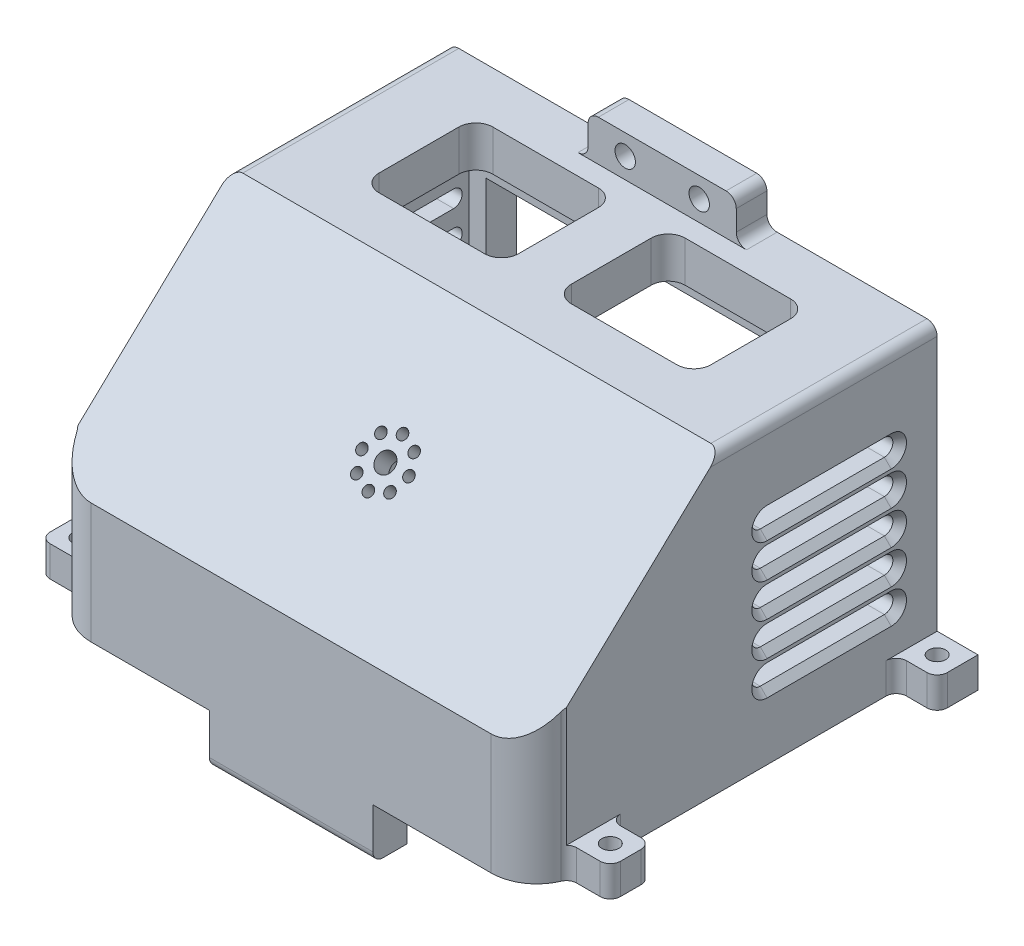
SolidWorks part; units mm, degrees
ref_plane "Front Plane" through (0, 0, 0) normal (0, 0, 1) x (1, 0, 0)
ref_plane "Top Plane" through (0, 0, 0) normal (0, 1, 0) x (1, 0, 0)
ref_plane "Right Plane" through (0, 0, 0) normal (1, 0, 0) x (0, 0, -1)
sketch "Sketch1" plane through (0, 0, 0) normal (0, 1, 0) x (1, 0, 0)
  line L0 (-83.8165, 105.1191) -> (-83.8165, 99.1191)
  line L1 (-80.8165, 96.1191) -> (-74.8165, 96.1191)
  line L2 (-71.8165, 93.1191) -> (-71.8165, 14.1191)
  line L3 (-74.8165, 11.1191) -> (-80.8165, 11.1191)
  line L4 (-83.8165, 8.1191) -> (-83.8165, -9.8809)
  line L5 (-80.8165, -12.8809) -> (-74.8165, -12.8809)
  line L6 (-71.8165, -15.8809) -> (-71.8165, -93.8809)
  line L7 (-74.8165, -96.8809) -> (-80.8165, -96.8809)
  line L8 (-83.8165, -99.8809) -> (-83.8165, -105.8809)
  line L9 (-80.8165, -108.8809) -> (-73.9507, -108.8809)
  line L10 (-58.8271, -118.8809) -> (-25.0665, -118.8809)
  line L12 (-25.0665, -108.8809) -> (-58.5665, -108.8809)
  line L13 (-58.5665, -108.8809) -> (-58.5665, -78.8809)
  line L14 (-58.5665, -78.8809) -> (-56.8165, -78.8809)
  line L15 (-56.8165, -78.8809) -> (-56.8165, 108.1191)
  line L16 (-56.8165, 108.1191) -> (56.6835, 108.1191)
  line L17 (56.6835, 108.1191) -> (56.6835, -78.8809)
  line L18 (56.6835, -78.8809) -> (58.4335, -78.8809)
  line L19 (58.4335, -78.8809) -> (58.4335, -108.8809)
  line L20 (58.4335, -108.8809) -> (24.9335, -108.8809)
  line L22 (24.9335, -118.8809) -> (58.6942, -118.8809)
  line L23 (73.8178, -108.8809) -> (80.6835, -108.8809)
  line L24 (83.6835, -105.8809) -> (83.6835, -99.8809)
  line L25 (80.6835, -96.8809) -> (74.6835, -96.8809)
  line L26 (71.6835, -93.8809) -> (71.6835, -15.8809)
  line L27 (74.6835, -12.8809) -> (80.6835, -12.8809)
  line L28 (83.6835, -9.8809) -> (83.6835, 8.1191)
  line L29 (80.6835, 11.1191) -> (74.6835, 11.1191)
  line L30 (71.6835, 14.1191) -> (71.6835, 93.1191)
  line L31 (74.6835, 96.1191) -> (80.6835, 96.1191)
  line L32 (83.6835, 99.1191) -> (83.6835, 105.1191)
  line L33 (80.6835, 108.1191) -> (73.5655, 108.1191)
  line L34 (56.6835, 118.1191) -> (-56.8165, 118.1191)
  line L35 (-73.6984, 108.1191) -> (-80.8165, 108.1191)
  line L36 (-83.8165, -0.8809) -> (83.6835, -0.8809)
  line L37 (-71.8165, -15.8809) -> (-71.8165, -0.8809)
  line L38 (71.6835, -15.8809) -> (71.6835, -0.8809)
  line L39 (-71.8165, -93.8809) -> (-71.8165, -109.7726)
  line L40 (71.6835, -93.8809) -> (71.6835, -109.7726)
  line L41 (-56.8165, -78.8809) -> (-56.8165, -108.8809)
  line L42 (56.6835, -78.8809) -> (56.6835, -108.8809)
  line L43 (-56.8165, -9.8809) -> (56.6835, -9.8809)
  line L44 (-25.0665, -108.8809) -> (24.9335, -108.8809)
  line L45 (-25.0665, -118.8809) -> (24.9335, -118.8809)
  arc A0 (-83.8165, 99.1191) -> (-80.8165, 96.1191) centre (-80.8165, 99.1191) ccw
  arc A1 (-71.8165, 93.1191) -> (-74.8165, 96.1191) centre (-74.8165, 93.1191) ccw
  arc A2 (-74.8165, 11.1191) -> (-71.8165, 14.1191) centre (-74.8165, 14.1191) ccw
  arc A3 (-80.8165, 11.1191) -> (-83.8165, 8.1191) centre (-80.8165, 8.1191) ccw
  arc A4 (-83.8165, -9.8809) -> (-80.8165, -12.8809) centre (-80.8165, -9.8809) ccw
  arc A5 (-71.8165, -15.8809) -> (-74.8165, -12.8809) centre (-74.8165, -15.8809) ccw
  arc A6 (-74.8165, -96.8809) -> (-71.8165, -93.8809) centre (-74.8165, -93.8809) ccw
  arc A7 (-80.8165, -96.8809) -> (-83.8165, -99.8809) centre (-80.8165, -99.8809) ccw
  arc A8 (-83.8165, -105.8809) -> (-80.8165, -108.8809) centre (-80.8165, -105.8809) ccw
  arc A9 (-71.1903, -110.7062) -> (-73.9507, -108.8809) centre (-73.9507, -111.8809) ccw
  arc A10 (-71.1903, -110.7062) -> (-58.8271, -118.8809) centre (-58.8271, -105.4448) ccw
  arc A11 (58.6942, -118.8809) -> (71.0574, -110.7062) centre (58.6942, -105.4448) ccw
  arc A12 (73.8178, -108.8809) -> (71.0574, -110.7062) centre (73.8178, -111.8809) ccw
  arc A13 (80.6835, -108.8809) -> (83.6835, -105.8809) centre (80.6835, -105.8809) ccw
  arc A14 (83.6835, -99.8809) -> (80.6835, -96.8809) centre (80.6835, -99.8809) ccw
  arc A15 (71.6835, -93.8809) -> (74.6835, -96.8809) centre (74.6835, -93.8809) ccw
  arc A16 (74.6835, -12.8809) -> (71.6835, -15.8809) centre (74.6835, -15.8809) ccw
  arc A17 (80.6835, -12.8809) -> (83.6835, -9.8809) centre (80.6835, -9.8809) ccw
  arc A18 (83.6835, 8.1191) -> (80.6835, 11.1191) centre (80.6835, 8.1191) ccw
  arc A19 (71.6835, 14.1191) -> (74.6835, 11.1191) centre (74.6835, 14.1191) ccw
  arc A20 (74.6835, 96.1191) -> (71.6835, 93.1191) centre (74.6835, 93.1191) ccw
  arc A21 (80.6835, 96.1191) -> (83.6835, 99.1191) centre (80.6835, 99.1191) ccw
  arc A22 (83.6835, 105.1191) -> (80.6835, 108.1191) centre (80.6835, 105.1191) ccw
  arc A23 (70.9345, 109.6775) -> (73.5655, 108.1191) centre (73.5655, 111.1191) ccw
  arc A24 (70.9345, 109.6775) -> (56.6835, 118.1191) centre (56.6835, 101.8691) ccw
  arc A25 (-56.8165, 118.1191) -> (-71.0675, 109.6775) centre (-56.8165, 101.8691) ccw
  arc A26 (-73.6984, 108.1191) -> (-71.0675, 109.6775) centre (-73.6984, 111.1191) ccw
  arc A27 (-80.8165, 108.1191) -> (-83.8165, 105.1191) centre (-80.8165, 105.1191) ccw
  dimension "D1" = 9
extrude "Boss-Extrude1" add sketch "Sketch1" along normal blind 87 contours A12 L40 L26 L38 L36 L17 L18 L19 L20 L44 L12 L13 L14 L15 L37 L6 L39 A9 A10 L10 L45 L22 A11 | L15 L43 L17 L36 | L18 L42 L20 L19 | L41 L14 L13 L12
sketch "Sketch2" plane through (0, 0, 0) normal (0, -1, 0) x (1, 0, 0)
  line L0 (-80.8165, 108.8809) -> (-73.9507, 108.8809) construction
  line L1 (73.8178, 108.8809) -> (80.6835, 108.8809) construction
  line L2 (83.6835, 105.8809) -> (83.6835, 99.8809) construction
  line L3 (80.6835, 96.8809) -> (74.6835, 96.8809) construction
  line L4 (58.6942, 118.8809) -> (-58.8271, 118.8809)
  line L5 (-71.8165, 109.7726) -> (-71.8165, 0.8809)
  line L6 (-71.8165, 0.8809) -> (71.6835, 0.8809)
  line L7 (71.6835, 0.8809) -> (71.6835, 109.7726)
  line L8 (58.6942, 118.8809) -> (-58.8271, 118.8809)
  line L9 (-71.8165, 109.7726) -> (-71.8165, 0.8809)
  line L10 (-71.8165, 0.8809) -> (71.6835, 0.8809)
  line L11 (71.6835, 0.8809) -> (71.6835, 109.7726)
  line L12 (74.6835, 12.8809) -> (80.6835, 12.8809) construction
  line L13 (83.6835, 9.8809) -> (83.6835, -8.1191) construction
  line L14 (-80.8165, 12.8809) -> (-74.8165, 12.8809) construction
  line L15 (-83.8165, -8.1191) -> (-83.8165, 9.8809) construction
  line L16 (-83.8165, 0.8809) -> (83.6835, 0.8809) construction
  line L17 (-74.8165, 96.8809) -> (-80.8165, 96.8809) construction
  line L18 (-83.8165, 99.8809) -> (-83.8165, 105.8809) construction
  line L19 (73.8178, 108.8809) -> (80.6835, 108.8809)
  line L20 (83.6835, 105.8809) -> (83.6835, 99.8809)
  line L21 (80.6835, 96.8809) -> (74.6835, 96.8809)
  line L22 (74.6835, 12.8809) -> (80.6835, 12.8809)
  line L23 (83.6835, 9.8809) -> (83.6835, 0.8809)
  line L24 (-80.8165, 12.8809) -> (-74.8165, 12.8809)
  line L25 (-83.8165, 0.8809) -> (-83.8165, 9.8809)
  line L26 (-83.8165, 0.8809) -> (83.6835, 0.8809)
  line L27 (-74.8165, 96.8809) -> (-80.8165, 96.8809)
  line L28 (-83.8165, 99.8809) -> (-83.8165, 105.8809)
  line L29 (-80.8165, 108.8809) -> (-73.9507, 108.8809)
  arc A0 (-83.8165, 99.8809) -> (-80.8165, 96.8809) centre (-80.8165, 99.8809) ccw construction
  arc A1 (71.0574, 110.7062) -> (73.8178, 108.8809) centre (73.8178, 111.8809) ccw construction
  arc A2 (83.6835, 105.8809) -> (80.6835, 108.8809) centre (80.6835, 105.8809) ccw construction
  arc A3 (80.6835, 96.8809) -> (83.6835, 99.8809) centre (80.6835, 99.8809) ccw construction
  arc A4 (71.0574, 110.7062) -> (71.6835, 109.7726) centre (73.8178, 111.8809) ccw
  arc A5 (71.0574, 110.7062) -> (58.6942, 118.8809) centre (58.6942, 105.4448) ccw
  arc A6 (-58.8271, 118.8809) -> (-71.1903, 110.7062) centre (-58.8271, 105.4448) ccw
  arc A7 (-71.8165, 109.7726) -> (-71.1903, 110.7062) centre (-73.9507, 111.8809) ccw
  arc A8 (71.0574, 110.7062) -> (71.6835, 109.7726) centre (73.8178, 111.8809) ccw
  arc A9 (71.0574, 110.7062) -> (58.6942, 118.8809) centre (58.6942, 105.4448) ccw
  arc A10 (-58.8271, 118.8809) -> (-71.1903, 110.7062) centre (-58.8271, 105.4448) ccw
  arc A11 (-71.8165, 109.7726) -> (-71.1903, 110.7062) centre (-73.9507, 111.8809) ccw
  arc A12 (74.6835, 96.8809) -> (71.6835, 93.8809) centre (74.6835, 93.8809) ccw construction
  arc A13 (71.6835, 15.8809) -> (74.6835, 12.8809) centre (74.6835, 15.8809) ccw construction
  arc A14 (83.6835, 9.8809) -> (80.6835, 12.8809) centre (80.6835, 9.8809) ccw construction
  arc A15 (-74.8165, 12.8809) -> (-71.8165, 15.8809) centre (-74.8165, 15.8809) ccw construction
  arc A16 (-80.8165, 12.8809) -> (-83.8165, 9.8809) centre (-80.8165, 9.8809) ccw construction
  arc A17 (-71.8165, 93.8809) -> (-74.8165, 96.8809) centre (-74.8165, 93.8809) ccw construction
  arc A18 (-80.8165, 108.8809) -> (-83.8165, 105.8809) centre (-80.8165, 105.8809) ccw construction
  arc A19 (-73.9507, 108.8809) -> (-71.1903, 110.7062) centre (-73.9507, 111.8809) ccw construction
  arc A20 (71.0574, 110.7062) -> (73.8178, 108.8809) centre (73.8178, 111.8809) ccw
  arc A21 (83.6835, 105.8809) -> (80.6835, 108.8809) centre (80.6835, 105.8809) ccw
  arc A22 (80.6835, 96.8809) -> (83.6835, 99.8809) centre (80.6835, 99.8809) ccw
  arc A23 (74.6835, 96.8809) -> (71.6835, 93.8809) centre (74.6835, 93.8809) ccw
  arc A24 (71.6835, 15.8809) -> (74.6835, 12.8809) centre (74.6835, 15.8809) ccw
  arc A25 (83.6835, 9.8809) -> (80.6835, 12.8809) centre (80.6835, 9.8809) ccw
  arc A26 (-74.8165, 12.8809) -> (-71.8165, 15.8809) centre (-74.8165, 15.8809) ccw
  arc A27 (-80.8165, 12.8809) -> (-83.8165, 9.8809) centre (-80.8165, 9.8809) ccw
  arc A28 (-71.8165, 93.8809) -> (-74.8165, 96.8809) centre (-74.8165, 93.8809) ccw
  arc A29 (-83.8165, 99.8809) -> (-80.8165, 96.8809) centre (-80.8165, 99.8809) ccw
  arc A30 (-80.8165, 108.8809) -> (-83.8165, 105.8809) centre (-80.8165, 105.8809) ccw
  arc A31 (-73.9507, 108.8809) -> (-71.1903, 110.7062) centre (-73.9507, 111.8809) ccw
  circle A33 centre (-77.8165, 6.8809) radius 2.5
  circle A34 centre (77.6835, 6.8809) radius 2.5
  circle A35 centre (77.6835, 102.8809) radius 2.5
  circle A36 centre (-77.8165, 102.8809) radius 2.5
  line M18 (-71.8165, 109.7726) -> (-71.8165, 0.8809)
  line M20 (71.6835, 0.8809) -> (71.6835, 109.7726)
  dimension "D2" = 5
  dimension "D3" = 5
  dimension "D4" = 5
  dimension "D5" = 5
  dimension "D1" = 0
extrude "Boss-Extrude2" add sketch "Sketch2" against normal blind 9 contours A23 L21 A22 L20 A21 L19 A20 L11 A35 | L23 A25 L22 A24 L26 A34 M20 | L24 A27 L25 L26 L9 A26 A33 | A31 L29 A30 L28 A29 L27 A28 A36 M18
sketch "Sketch3" plane through (0, 87, 0) normal (0, 1, 0) x (1, 0, 0)
  line L0 (56.6835, -108.8809) -> (-56.8165, -108.8809) construction
  line L1 (56.6835, -9.8809) -> (56.6835, -108.8809) construction
  line L2 (-56.8165, -108.8809) -> (-56.8165, -9.8809) construction
  line L3 (-56.8165, -9.8809) -> (56.6835, -9.8809) construction
  line L4 (56.6835, -108.8809) -> (-56.8165, -108.8809)
  line L5 (56.6835, -9.8809) -> (56.6835, -108.8809)
  line L6 (-56.8165, -108.8809) -> (-56.8165, -9.8809)
  line L7 (-56.8165, -9.8809) -> (56.6835, -9.8809)
extrude "Boss-Extrude3" add sketch "Sketch3" against normal blind 12
sketch "Sketch4" plane through (-71.8165, 0, 0) normal (-1, 0, 0) x (0, 0, 1)
  line L0 (55.3268, 87) -> (109.7726, 35)
  line L1 (93.8809, 0) -> (109.7726, 0) construction
  line L2 (64.3268, 87) -> (109.7726, 44)
  line L8 (93.8809, 0) -> (93.8809, 9)
  line L9 (93.8809, 9) -> (109.7726, 9)
  line L10 (109.7726, 9) -> (109.7726, 87)
  line L11 (109.7726, 87) -> (0.8809, 87)
  line L12 (0.8809, 87) -> (0.8809, 9)
  line L13 (0.8809, 9) -> (15.8809, 9)
  line L14 (15.8809, 9) -> (15.8809, 0)
  line L15 (15.8809, 0) -> (93.8809, 0)
  line L16 (93.8809, 0) -> (93.8809, 9)
  line L17 (93.8809, 9) -> (109.7726, 9)
  line L18 (109.7726, 9) -> (109.7726, 87)
  line L19 (109.7726, 87) -> (0.8809, 87)
  line L20 (0.8809, 87) -> (0.8809, 9)
  line L21 (0.8809, 9) -> (15.8809, 9)
  line L22 (15.8809, 9) -> (15.8809, 0)
  line L23 (15.8809, 0) -> (93.8809, 0)
  line M11 (109.7726, 9) -> (109.7726, 87)
  line M12 (109.7726, 87) -> (0.8809, 87)
  dimension "D2" = 35
  dimension "D3" = 9
  dimension "D4" = 9
  dimension "D1" = 0
extrude "Boss-Extrude4" add sketch "Sketch4" against normal blind 140 contours L2 L0 M12 M11
sketch "Sketch5" plane through (71.6835, 0, 0) normal (1, 0, 0) x (0, 0, -1)
  line L0 (-64.3268, 87) -> (-109.7726, 44) construction
  line L1 (-64.3268, 87) -> (-118.8809, 35.3819)
  line L2 (-109.7726, 87) -> (-0.8809, 87) construction
  line L3 (-118.8809, 87) -> (-118.8809, 0) construction
  line L4 (-109.7726, 87) -> (-64.3268, 87)
  line L5 (-118.8809, 87) -> (-118.8809, 35.3819)
  line L7 (-118.8809, 87) -> (-109.7726, 87)
extrude "Cut-Extrude1" cut sketch "Sketch5" against normal blind 144
sketch "Sketch6" plane through (0, 0, 0.8809) normal (0, 0, -1) x (-1, 0, 0)
  line L0 (-71.6835, 87) -> (-71.6835, 9) construction
  line L1 (-51.6835, 67) -> (51.8165, 67)
  line L2 (-51.6835, 67) -> (-51.6835, 30)
  line L3 (-51.6835, 30) -> (51.8165, 30)
  line L4 (51.8165, 67) -> (51.8165, 30)
  line L5 (-51.6835, 67) -> (51.8165, 30) construction
  line L6 (-51.6835, 30) -> (51.8165, 67) construction
  line L7 (71.8165, 9) -> (71.8165, 87) construction
  line L8 (71.8165, 87) -> (-71.6835, 87) construction
  line L9 (-56.6835, 0) -> (56.8165, 0) construction
  point P0 (0.0665, 48.5)
  dimension "D1" = 20
  dimension "D2" = 20
  dimension "D3" = 20
  dimension "D4" = 30
extrude "Cut-Extrude2" cut sketch "Sketch6" against normal blind 9
fillet "Fillet1" radius 3 2 edges at (71.6835, 87, 32.6038) (-71.8165, 87, 32.6038)
sketch "Sketch7" plane through (0, 0, 0.8809) normal (0, 0, -1) x (-1, 0, 0)
  line L0 (-21.6835, 87) -> (-21.6835, 99)
  line L1 (-21.6835, 99) -> (21.8165, 99)
  line L2 (21.8165, 99) -> (21.8165, 87)
  line L8 (68.8165, 87) -> (-68.6835, 87)
  line L9 (-71.6835, 84) -> (-71.6835, 9)
  line L10 (-71.6835, 9) -> (-83.6835, 9)
  line L11 (-83.6835, 9) -> (-83.6835, 0)
  line L12 (-83.6835, 0) -> (83.8165, 0)
  line L13 (83.8165, 0) -> (83.8165, 9)
  line L14 (83.8165, 9) -> (71.8165, 9)
  line L15 (71.8165, 9) -> (71.8165, 84)
  line L16 (68.8165, 87) -> (-68.6835, 87)
  line L17 (-71.6835, 84) -> (-71.6835, 9)
  line L18 (-71.6835, 9) -> (-83.6835, 9)
  line L19 (-83.6835, 9) -> (-83.6835, 0)
  line L20 (-83.6835, 0) -> (83.8165, 0)
  line L21 (83.8165, 0) -> (83.8165, 9)
  line L22 (83.8165, 9) -> (71.8165, 9)
  line L23 (71.8165, 9) -> (71.8165, 84)
  circle A0 centre (-10.8035, 93) radius 3
  circle A1 centre (10.9365, 93) radius 3
  arc A2 (-68.6835, 87) -> (-71.6835, 84) centre (-68.6835, 84) ccw
  arc A3 (71.8165, 84) -> (68.8165, 87) centre (68.8165, 84) ccw
  arc A4 (-68.6835, 87) -> (-71.6835, 84) centre (-68.6835, 84) ccw
  arc A5 (71.8165, 84) -> (68.8165, 87) centre (68.8165, 84) ccw
  line M18 (68.8165, 87) -> (-68.6835, 87)
  dimension "D5" = 6
  dimension "D6" = 6
  dimension "D2" = 50
  dimension "D3" = 50
  dimension "D4" = 12
  dimension "D7" = 6
  dimension "D8" = 6
  dimension "D9" = 10.88
  dimension "D10" = 10.88
  dimension "D1" = 0
extrude "Boss-Extrude5" add sketch "Sketch7" against normal blind 9 contours L2 L1 L0 A1 A0 M18
fillet "Fillet2" radius 3 4 edges at (-21.8165, 87, 5.3809) (-21.8165, 99, 5.3809) (21.6835, 99, 5.3809) (21.6835, 87, 5.3809)
sketch "Sketch8" plane through (0, 78.0182, 73.8194) normal (0, 0.7264, 0.6873) x (1, 0, 0)
  line L0 (-63.9989, 13.0684) -> (-71.8165, 13.0684) construction
  line L1 (-68.8165, 13.0684) -> (68.6835, 13.0684) construction
  line L2 (-71.8165, 67.6401) -> (-71.8165, 10.2559) construction
  line L3 (-71.8165, 13.0684) -> (-71.8165, 10.2559) construction
  line L4 (-71.8165, -49.4962) -> (-71.8165, -62.0079) construction
  line L5 (-71.8165, -62.0079) -> (-58.8271, -62.0355) construction
  line L6 (58.6942, -62.0355) -> (71.6835, -62.0355) construction
  line L7 (71.6835, -68.1935) -> (71.6835, -11.5356) construction
  line L8 (71.6835, -62.0355) -> (71.6835, -49.4962) construction
  line L9 (68.6835, 13.0684) -> (71.6835, 13.0684) construction
  line L10 (71.6835, 10.2559) -> (71.6835, 67.6401) construction
  line L11 (71.6835, 13.0684) -> (71.6835, 8.7034) construction
  line L12 (-71.8165, 10.2559) -> (-71.8165, 8.7034) construction
  line L13 (-71.8165, 13.0684) -> (71.6835, -62.0355) construction
  line L14 (-71.8165, -62.0079) -> (71.6835, 13.0684) construction
  circle A0 centre (0.1633, -24.1993) radius 2.75
  circle A1 centre (7.0683, -24.1993) radius 1.5
  circle A2 centre (5.0459, -29.0819) radius 1.5
  circle A3 centre (0.1633, -31.1043) radius 1.5
  circle A4 centre (-4.7193, -29.0819) radius 1.5
  circle A5 centre (-6.7417, -24.1993) radius 1.5
  circle A6 centre (-4.7193, -19.3168) radius 1.5
  circle A7 centre (0.1633, -17.2943) radius 1.5
  circle A8 centre (5.0459, -19.3168) radius 1.5
  point P26 (-0.0665, -24.4836)
  point P30 (-108.6096, 10.2559)
  point P52 (0.1633, -24.1993)
  dimension "D1" = 5.5
  dimension "D3" = 3
  dimension "D2" = 6.905
extrude "Cut-Extrude3" cut sketch "Sketch8" against normal blind 9
sketch "Sketch11" plane through (0, 0, 0) normal (0, -1, 0) x (1, 0, 0)
  line L0 (-25.0665, 118.8809) -> (-25.0665, 108.8809) construction
  line L1 (24.9335, 118.8809) -> (24.9335, 108.8809) construction
  line L2 (-25.0665, 118.8809) -> (24.9335, 118.8809) construction
  line L3 (-24.0665, 118.8809) -> (23.9335, 118.8809)
  line L4 (23.9335, 118.8809) -> (23.9335, 108.8809)
  line L5 (-25.0665, 108.8809) -> (24.9335, 108.8809) construction
  line L6 (23.9335, 108.8809) -> (-24.0665, 108.8809)
  line L7 (-24.0665, 108.8809) -> (-24.0665, 118.8809)
  dimension "D1" = 1
  dimension "D2" = 1
extrude "Boss-Extrude6" add sketch "Sketch11" along normal blind 15
fillet "Fillet3" radius 3 1 edges at (-0.0665, -15, 118.8809)
sketch "Sketch12" plane through (0, 87, 0) normal (0, 1, 0) x (1, 0, 0)
  line L1 (-48.8165, -15.8809) -> (48.6835, -15.8809)
  line L2 (-48.8165, -15.8809) -> (-48.8165, -49.3268)
  line L3 (-48.8165, -49.3268) -> (48.6835, -49.3268)
  line L4 (48.6835, -15.8809) -> (48.6835, -49.3268)
  line L5 (-48.8165, -15.8809) -> (48.6835, -49.3268) construction
  line L6 (-48.8165, -49.3268) -> (48.6835, -15.8809) construction
  line L8 (24.6835, -9.8809) -> (-24.8165, -9.8809)
  line L9 (-24.8165, -9.8809) -> (-24.8165, -0.8809)
  line L10 (-24.8165, -0.8809) -> (-68.8165, -0.8809)
  line L11 (-68.8165, -0.8809) -> (-68.8165, -64.3268)
  line L12 (-68.8165, -64.3268) -> (68.6835, -64.3268)
  line L13 (68.6835, -64.3268) -> (68.6835, -0.8809)
  line L14 (68.6835, -0.8809) -> (24.6835, -0.8809)
  line L15 (24.6835, -0.8809) -> (24.6835, -9.8809)
  line L16 (24.6835, -9.8809) -> (-24.8165, -9.8809)
  line L17 (-24.8165, -9.8809) -> (-24.8165, -0.8809)
  line L19 (-68.8165, -0.8809) -> (-68.8165, -64.3268)
  line L20 (-68.8165, -64.3268) -> (68.6835, -64.3268)
  line L21 (68.6835, -64.3268) -> (68.6835, -0.8809)
  line L22 (68.6835, -0.8809) -> (24.6835, -0.8809)
  line L23 (24.6835, -0.8809) -> (24.6835, -9.8809)
  point P2 (-0.0665, -32.6038)
  dimension "D2" = 20
  dimension "D3" = 20
  dimension "D5" = 15
  dimension "D1" = 0
extrude "Cut-Extrude4" cut sketch "Sketch12" against normal blind 12 contours L4 L1 L2 L3
fillet "Fillet4" radius 5 4 edges at (-48.8165, 81, 15.8809) (-48.8165, 81, 49.3268) (48.6835, 81, 49.3268) (48.6835, 81, 15.8809)
sketch "Sketch13" plane through (0, 0, 15.8809) normal (0, 0, 1) x (1, 0, 0)
  line L0 (-43.8165, 87) -> (43.6835, 87) construction
  line L1 (-7.8165, 87) -> (-7.8165, 75)
  line L2 (-43.8165, 75) -> (43.6835, 75) construction
  line L3 (-7.8165, 75) -> (7.6835, 75)
  line L4 (7.6835, 75) -> (7.6835, 87)
  line L5 (7.6835, 87) -> (-7.8165, 87)
  line L6 (-43.8165, 87) -> (-43.8165, 75) construction
  line L7 (43.6835, 75) -> (43.6835, 87) construction
  dimension "D1" = 36
  dimension "D2" = 36
extrude "Boss-Extrude7" add sketch "Sketch13" along normal blind 34
fillet "Fillet5" radius 5 4 edges at (-7.8165, 81, 15.8809) (-7.8165, 81, 49.3268) (7.6835, 81, 49.3268) (7.6835, 81, 15.8809)
sketch "Sketch14" plane through (-71.8165, 0, 0) normal (-1, 0, 0) x (0, 0, 1)
  line L0 (55.3268, 87) -> (109.7726, 35) construction
  line L1 (9.8809, 96) -> (9.8809, 90) construction
  line L2 (55.3268, 87) -> (109.7726, 35)
  line L3 (9.8809, 96) -> (9.8809, 90)
  line L4 (9.8809, 87) -> (9.8809, 18.6092) construction
  line L5 (55.3268, 87) -> (55.3268, 18.6092) construction
  line L6 (14.3809, 64) -> (50.8268, 64)
  line L7 (50.8268, 59) -> (14.3809, 59)
  line L8 (67.4974, 84) -> (0.8809, 84) construction
  line L9 (50.8268, 49) -> (14.3809, 49)
  line L10 (14.3809, 54) -> (50.8268, 54)
  line L11 (50.8268, 39) -> (14.3809, 39)
  line L12 (14.3809, 44) -> (50.8268, 44)
  line L13 (50.8268, 49) -> (14.3809, 49)
  line L14 (14.3809, 54) -> (50.8268, 54)
  line L15 (50.8268, 29) -> (14.3809, 29)
  line L16 (14.3809, 34) -> (50.8268, 34)
  line L17 (50.8268, 19) -> (14.3809, 19)
  line L18 (14.3809, 24) -> (50.8268, 24)
  line L19 (50.8268, 29) -> (14.3809, 29)
  line L20 (14.3809, 34) -> (50.8268, 34)
  circle A0 centre (14.3809, 61.5) radius 2.5
  circle A1 centre (50.8268, 61.5) radius 2.5
  circle A2 centre (14.3809, 51.5) radius 2.5
  circle A3 centre (50.8268, 51.5) radius 2.5
  circle A4 centre (14.3809, 41.5) radius 2.5
  circle A5 centre (50.8268, 41.5) radius 2.5
  circle A6 centre (14.3809, 51.5) radius 2.5
  circle A7 centre (50.8268, 51.5) radius 2.5
  circle A8 centre (14.3809, 31.5) radius 2.5
  circle A9 centre (50.8268, 31.5) radius 2.5
  circle A10 centre (14.3809, 21.5) radius 2.5
  circle A11 centre (50.8268, 21.5) radius 2.5
  circle A12 centre (14.3809, 31.5) radius 2.5
  circle A13 centre (50.8268, 31.5) radius 2.5
  dimension "D3" = 5
  dimension "D4" = 5
  dimension "D1" = 9
  dimension "D2" = 9
  dimension "D5" = 20
  dimension "D6" = 2
  dimension "D7" = 2
  dimension "D8" = 2
  dimension "D9" = 2
extrude "Cut-Extrude5" cut sketch "Sketch14" against normal blind 143.5 contours A10 | A11 L18 A10 L17 | A11 | A8 | A9 L16 A8 L15 | A9 | A4 | A5 L12 A4 L11 | A5 | A2 | A3 L10 A2 L9 | A3 | A0 | A1 L6 A0 L7 | A1
chamfer "Chamfer1" distance 2 angle 45 40 edges at (-71.8165, 21.5, 53.3268) (-71.8165, 24, 32.6038) (-71.8165, 21.5, 11.8809) (-71.8165, 19, 32.6038) (-71.8165, 31.5, 53.3268) (-71.8165, 34, 32.6038) (-71.8165, 31.5, 11.8809) (-71.8165, 29, 32.6038) (-71.8165, 44, 32.6038) (-71.8165, 41.5, 11.8809) (-71.8165, 39, 32.6038) (-71.8165, 41.5, 53.3268) (-71.8165, 51.5, 53.3268) (-71.8165, 54, 32.6038) (-71.8165, 51.5, 11.8809) (-71.8165, 49, 32.6038) (-71.8165, 61.5, 11.8809) (-71.8165, 59, 32.6038) (-71.8165, 61.5, 53.3268) (-71.8165, 64, 32.6038) (71.6835, 19, 32.6038) (71.6835, 21.5, 11.8809) (71.6835, 24, 32.6038) (71.6835, 21.5, 53.3268) (71.6835, 31.5, 11.8809) (71.6835, 29, 32.6038) (71.6835, 34, 32.6038) (71.6835, 31.5, 53.3268) (71.6835, 41.5, 11.8809) (71.6835, 39, 32.6038) (71.6835, 44, 32.6038) (71.6835, 41.5, 53.3268) (71.6835, 51.5, 53.3268) (71.6835, 54, 32.6038) (71.6835, 49, 32.6038) (71.6835, 51.5, 11.8809) (71.6835, 64, 32.6038) (71.6835, 61.5, 11.8809) (71.6835, 59, 32.6038) (71.6835, 61.5, 53.3268)
